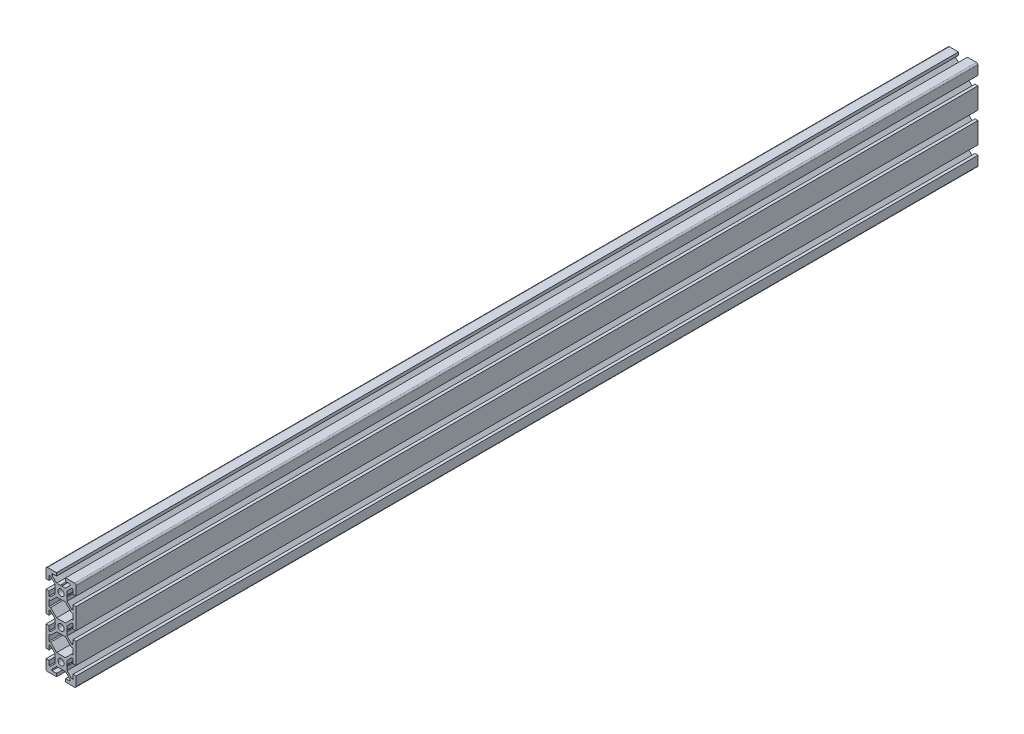
SolidWorks part; units mm, degrees
material "6061 Alloy"
ref_plane "Front Plane" through (0, 0, 0) normal (0, 0, 1) x (1, 0, 0)
ref_plane "Top Plane" through (0, 0, 0) normal (0, 1, 0) x (1, 0, 0)
ref_plane "Right Plane" through (0, 0, 0) normal (1, 0, 0) x (0, 0, -1)
ref_plane "Plane1" through (0, 0, 0) normal (0, 0, 1) x (1, 0, 0)
sketch "Sketch1" plane through (0, 0, 0) normal (0, 0, 1) x (1, 0, 0)
  line L0 (-10, -17) -> (-8, -17)
  line L1 (-8, -17) -> (-8, -14)
  line L2 (-8, -14) -> (-7.0607, -14)
  line L3 (-7.0607, -14) -> (-4, -17.0607)
  line L4 (-4, -17.0607) -> (-4, -19.4804)
  line L5 (-4, -19.4804) -> (-3.7, -20)
  line L6 (-3.7, -20) -> (-4, -20.5196)
  line L7 (-4, -20.5196) -> (-4, -22.9393)
  line L8 (-4, -22.9393) -> (-7.0607, -26)
  line L9 (-7.0607, -26) -> (-8, -26)
  line L10 (-8, -26) -> (-8, -23)
  line L11 (-8, -23) -> (-10, -23)
  line L12 (-10, -23) -> (-10, -29)
  line L13 (-9, -30) -> (-3, -30)
  line L14 (-3, -30) -> (-3, -28)
  line L15 (-3, -28) -> (-6, -28)
  line L16 (-6, -28) -> (-6, -27.0607)
  line L17 (-6, -27.0607) -> (-2.9393, -24)
  line L18 (-2.9393, -24) -> (-0.5196, -24)
  line L19 (-0.5196, -24) -> (0, -23.7)
  line L20 (0, -23.7) -> (0.5196, -24)
  line L21 (0.5196, -24) -> (2.9393, -24)
  line L22 (2.9393, -24) -> (6, -27.0607)
  line L23 (6, -27.0607) -> (6, -28)
  line L24 (6, -28) -> (3, -28)
  line L25 (3, -28) -> (3, -30)
  line L26 (3, -30) -> (9, -30)
  line L27 (10, -29) -> (10, -23)
  line L28 (10, -23) -> (8, -23)
  line L29 (8, -23) -> (8, -26)
  line L30 (8, -26) -> (7.0607, -26)
  line L31 (7.0607, -26) -> (4, -22.9393)
  line L32 (4, -22.9393) -> (4, -20.5196)
  line L33 (4, -20.5196) -> (3.7, -20)
  line L34 (3.7, -20) -> (4, -19.4804)
  line L35 (4, -19.4804) -> (4, -17.0607)
  line L36 (4, -17.0607) -> (7.0607, -14)
  line L37 (7.0607, -14) -> (8, -14)
  line L38 (8, -14) -> (8, -17)
  line L39 (8, -17) -> (10, -17)
  line L40 (10, -17) -> (10, -3)
  line L41 (10, -3) -> (8, -3)
  line L42 (8, -3) -> (8, -6)
  line L43 (8, -6) -> (7.0607, -6)
  line L44 (7.0607, -6) -> (4, -2.9393)
  line L45 (4, -2.9393) -> (4, -0.5196)
  line L46 (4, -0.5196) -> (3.7, 0)
  line L47 (3.7, 0) -> (4, 0.5196)
  line L48 (4, 0.5196) -> (4, 2.9393)
  line L49 (4, 2.9393) -> (7.0607, 6)
  line L50 (7.0607, 6) -> (8, 6)
  line L51 (8, 6) -> (8, 3)
  line L52 (8, 3) -> (10, 3)
  line L53 (10, 3) -> (10, 17)
  line L54 (10, 17) -> (8, 17)
  line L55 (8, 17) -> (8, 14)
  line L56 (8, 14) -> (7.0607, 14)
  line L57 (7.0607, 14) -> (4, 17.0607)
  line L58 (4, 17.0607) -> (4, 19.4804)
  line L59 (4, 19.4804) -> (3.7, 20)
  line L60 (3.7, 20) -> (4, 20.5196)
  line L61 (4, 20.5196) -> (4, 22.9393)
  line L62 (4, 22.9393) -> (7.0607, 26)
  line L63 (7.0607, 26) -> (8, 26)
  line L64 (8, 26) -> (8, 23)
  line L65 (8, 23) -> (10, 23)
  line L66 (10, 23) -> (10, 29)
  line L67 (9, 30) -> (3, 30)
  line L68 (3, 30) -> (3, 28)
  line L69 (3, 28) -> (6, 28)
  line L70 (6, 28) -> (6, 27.0607)
  line L71 (6, 27.0607) -> (2.9393, 24)
  line L72 (2.9393, 24) -> (0.5196, 24)
  line L73 (0.5196, 24) -> (0, 23.7)
  line L74 (0, 23.7) -> (-0.5196, 24)
  line L75 (-0.5196, 24) -> (-2.9393, 24)
  line L76 (-2.9393, 24) -> (-6, 27.0607)
  line L77 (-6, 27.0607) -> (-6, 28)
  line L78 (-6, 28) -> (-3, 28)
  line L79 (-3, 28) -> (-3, 30)
  line L80 (-3, 30) -> (-9, 30)
  line L81 (-10, 29) -> (-10, 23)
  line L82 (-10, 23) -> (-8, 23)
  line L83 (-8, 23) -> (-8, 26)
  line L84 (-8, 26) -> (-7.0607, 26)
  line L85 (-7.0607, 26) -> (-4, 22.9393)
  line L86 (-4, 22.9393) -> (-4, 20.5196)
  line L87 (-4, 20.5196) -> (-3.7, 20)
  line L88 (-3.7, 20) -> (-4, 19.4804)
  line L89 (-4, 19.4804) -> (-4, 17.0607)
  line L90 (-4, 17.0607) -> (-7.0607, 14)
  line L91 (-7.0607, 14) -> (-8, 14)
  line L92 (-8, 14) -> (-8, 17)
  line L93 (-8, 17) -> (-10, 17)
  line L94 (-10, 17) -> (-10, 3)
  line L95 (-10, 3) -> (-8, 3)
  line L96 (-8, 3) -> (-8, 6)
  line L97 (-8, 6) -> (-7.0607, 6)
  line L98 (-7.0607, 6) -> (-4, 2.9393)
  line L99 (-4, 2.9393) -> (-4, 0.5196)
  line L100 (-4, 0.5196) -> (-3.7, 0)
  line L101 (-3.7, 0) -> (-4, -0.5196)
  line L102 (-4, -0.5196) -> (-4, -2.9393)
  line L103 (-4, -2.9393) -> (-7.0607, -6)
  line L104 (-7.0607, -6) -> (-8, -6)
  line L105 (-8, -6) -> (-8, -3)
  line L106 (-8, -3) -> (-10, -3)
  line L107 (-10, -3) -> (-10, -17)
  line L108 (-8, 8) -> (-6.9393, 8)
  line L109 (-6.9393, 8) -> (-2.9393, 4)
  line L110 (-2.9393, 4) -> (2.9393, 4)
  line L111 (2.9393, 4) -> (6.9393, 8)
  line L112 (6.9393, 8) -> (8, 8)
  line L113 (8, 8) -> (8, 12)
  line L114 (8, 12) -> (6.9393, 12)
  line L115 (6.9393, 12) -> (2.9393, 16)
  line L116 (2.9393, 16) -> (-2.9393, 16)
  line L117 (-2.9393, 16) -> (-6.9393, 12)
  line L118 (-6.9393, 12) -> (-8, 12)
  line L119 (-8, 12) -> (-8, 8)
  line L120 (-8, -8) -> (-8, -12)
  line L121 (-8, -12) -> (-6.9393, -12)
  line L122 (-6.9393, -12) -> (-2.9393, -16)
  line L123 (-2.9393, -16) -> (2.9393, -16)
  line L124 (2.9393, -16) -> (6.9393, -12)
  line L125 (6.9393, -12) -> (8, -12)
  line L126 (8, -12) -> (8, -8)
  line L127 (8, -8) -> (6.9393, -8)
  line L128 (6.9393, -8) -> (2.9393, -4)
  line L129 (2.9393, -4) -> (-2.9393, -4)
  line L130 (-2.9393, -4) -> (-6.9393, -8)
  line L131 (-6.9393, -8) -> (-8, -8)
  arc A0 (-10, -29) -> (-9, -30) centre (-9, -29) ccw
  arc A1 (9, -30) -> (10, -29) centre (9, -29) ccw
  arc A2 (10, 29) -> (9, 30) centre (9, 29) ccw
  arc A3 (-9, 30) -> (-10, 29) centre (-9, 29) ccw
extrude "Boss-Extrude1" add sketch "Sketch1" against normal blind 600
ref_plane "Plane2" through (0, 0, 0) normal (1, 0, 0) x (0, 0, -1)
sketch "Sketch2" plane through (0, 0, 0) normal (1, 0, 0) x (0, 0, -1)
  line L0 (600, 20) -> (600, 17.9)
  line L1 (600, 17.9) -> (0, 17.9)
  line L2 (0, 17.9) -> (0, 20)
  line L3 (0, 20) -> (600, 20)
  line L4 (0, 20) -> (600, 20) construction
revolve "Cut-Revolve1" cut sketch "Sketch2" angle 360 about L4
ref_plane "Plane3" through (0, 0, 0) normal (1, 0, 0) x (0, 0, -1)
sketch "Sketch3" plane through (0, 0, 0) normal (1, 0, 0) x (0, 0, -1)
  line L0 (600, 0) -> (600, -2.1)
  line L1 (600, -2.1) -> (0, -2.1)
  line L2 (0, -2.1) -> (0, 0)
  line L3 (0, 0) -> (600, 0)
  line L4 (0, 0) -> (600, 0) construction
revolve "Cut-Revolve2" cut sketch "Sketch3" angle 360 about L4
ref_plane "Plane4" through (0, 0, 0) normal (1, 0, 0) x (0, 0, -1)
sketch "Sketch4" plane through (0, 0, 0) normal (1, 0, 0) x (0, 0, -1)
  line L0 (600, -20) -> (600, -22.1)
  line L1 (600, -22.1) -> (0, -22.1)
  line L2 (0, -22.1) -> (0, -20)
  line L3 (0, -20) -> (600, -20)
  line L4 (0, -20) -> (600, -20) construction
revolve "Cut-Revolve3" cut sketch "Sketch4" angle 360 about L4
